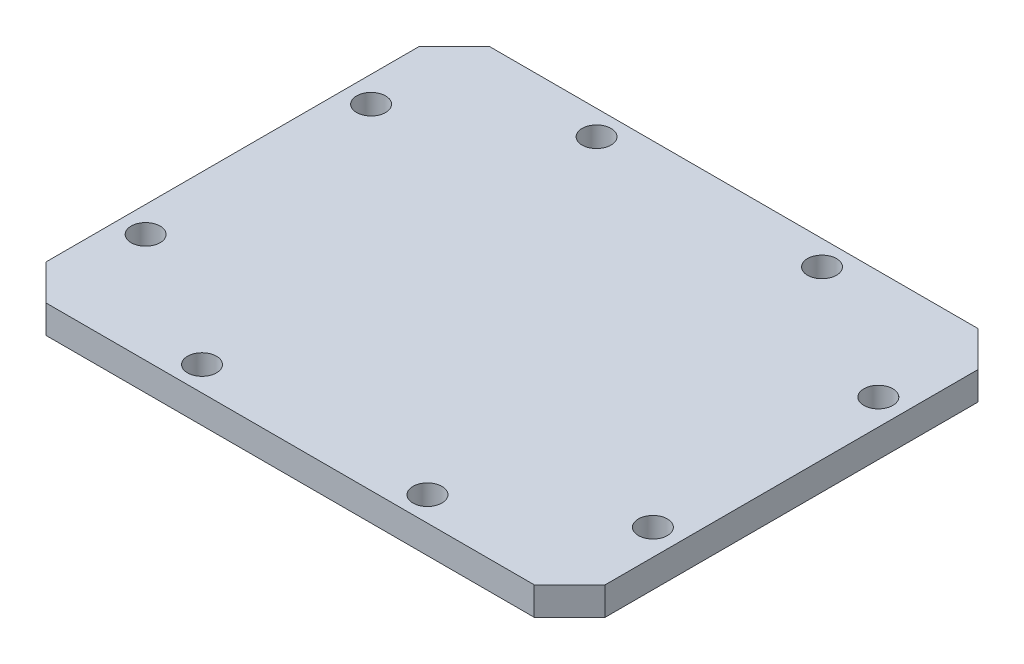
SolidWorks part; units mm, degrees
ref_plane "Front Plane" through (0, 0, 0) normal (0, 0, 1) x (1, 0, 0)
ref_plane "Top Plane" through (0, 0, 0) normal (0, 1, 0) x (1, 0, 0)
ref_plane "Right Plane" through (0, 0, 0) normal (1, 0, 0) x (0, 0, -1)
sketch "Sketch1" plane through (0, 0, 0) normal (0, 1, 0) x (1, 0, 0)
  line L1 (0, 0) -> (63, 0)
  line L2 (0, 0) -> (0, -50)
  line L3 (0, -50) -> (63, -50)
  line L4 (63, 0) -> (63, -50)
  line L5 (6.1, -5.95) -> (56.9, -5.95) construction
  line L6 (6.1, -5.95) -> (6.1, -44.05) construction
  line L7 (6.1, -44.05) -> (56.9, -44.05) construction
  line L8 (56.9, -5.95) -> (56.9, -44.05) construction
  circle A0 centre (18.8, -2.775) radius 1.632
  circle A1 centre (44.2, -2.775) radius 1.6319
  circle A2 centre (60.075, -12.3) radius 1.6319
  circle A3 centre (60.075, -37.7) radius 1.6319
  circle A4 centre (44.2, -47.225) radius 1.6319
  circle A5 centre (18.8, -47.225) radius 1.6319
  circle A6 centre (2.925, -37.7) radius 1.6319
  circle A7 centre (2.925, -12.3) radius 1.632
  dimension "D7" = 3.2639
  dimension "D1" = 63
  dimension "D2" = 50
  dimension "D3" = 50.8
  dimension "D4" = 38.1
  dimension "D5" = 6.1
  dimension "D6" = 5.95
  dimension "D8" = 25.4
  dimension "D9" = 25.4
  dimension "D10" = 3.175
  dimension "D11" = 3.175
  dimension "D12" = 3.175
  dimension "D13" = 3.175
  dimension "D14" = 12.7
  dimension "D15" = 6.35
extrude "Boss-Extrude1" add sketch "Sketch1" along normal blind 3.175
chamfer "Chamfer1" distance 4 angle 45 4 edges at (0, 1.5875, 0) (63, 1.5875, 0) (0, 1.5875, 50) (63, 1.5875, 50)
equation "\"D5@Sketch1\"=(\"D1@Sketch1\"-\"D3@Sketch1\")/2"
equation "\"D6@Sketch1\"=(\"D2@Sketch1\"-\"D4@Sketch1\")/2"
equation "\"D9@Sketch1\"=\"D8@Sketch1\""
equation "\"D11@Sketch1\"=\"D10@Sketch1\""
equation "\"D12@Sketch1\"=\"D10@Sketch1\""
equation "\"D13@Sketch1\"=\"D12@Sketch1\""
equation "\"D14@Sketch1\"=(\"D3@Sketch1\"-\"D8@Sketch1\")/2"
equation "\"D15@Sketch1\"=(\"D4@Sketch1\"-\"D9@Sketch1\")/2"
